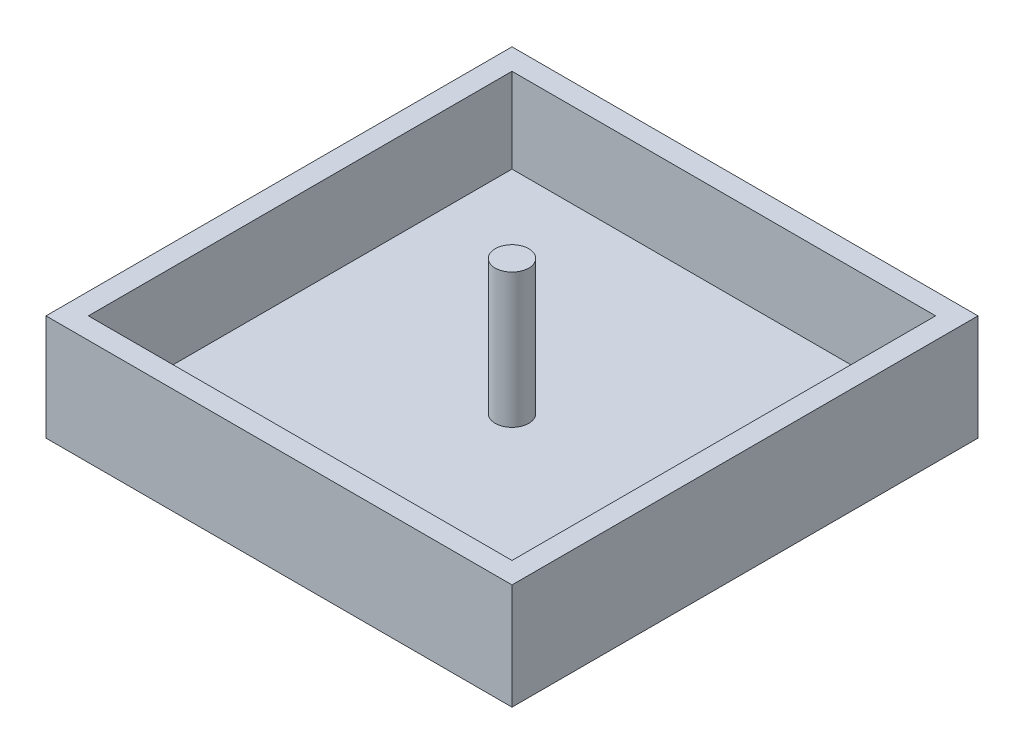
SolidWorks part; units mm, degrees
ref_plane "Plano frontal" through (0, 0, 0) normal (0, 0, 1) x (1, 0, 0)
ref_plane "Plano superior" through (0, 0, 0) normal (0, 1, 0) x (1, 0, 0)
ref_plane "Plano direito" through (0, 0, 0) normal (1, 0, 0) x (0, 0, -1)
sketch "Esboço1" plane through (0, 0, 0) normal (0, 1, 0) x (1, 0, 0)
  line L1 (-35.0121, 4.9879) -> (4.9879, 4.9879)
  line L2 (-35.0121, 4.9879) -> (-35.0121, -35.0121)
  line L3 (-35.0121, -35.0121) -> (4.9879, -35.0121)
  line L4 (4.9879, 4.9879) -> (4.9879, -35.0121)
extrude "Ressalto-extrusão1" add sketch "Esboço1" along normal blind 2
sketch "Esboço2" plane through (0, 0, 0) normal (0, -1, 0) x (1, 0, 0)
  line L0 (-35.0121, 35.0121) -> (-35.0121, -4.9879)
  line L1 (-37.0121, 35.0121) -> (-37.0121, -6.9879)
  line L2 (-35.0121, -4.9879) -> (4.9879, -4.9879)
  line L3 (-35.0121, -6.9879) -> (-37.0121, -6.9879)
  line L4 (-37.0121, -6.9879) -> (6.9879, -6.9879)
  line L5 (4.9879, -4.9879) -> (4.9879, 35.0121)
  line L6 (6.9879, -4.9879) -> (6.9879, -6.9879)
  line L7 (6.9879, -6.9879) -> (6.9879, 37.0121)
  line L8 (4.9879, 35.0121) -> (-35.0121, 35.0121)
  line L9 (4.9879, 37.0121) -> (6.9879, 37.0121)
  line L10 (6.9879, 37.0121) -> (-37.0121, 37.0121)
  line L11 (-37.0121, 35.0121) -> (-37.0121, 37.0121)
  line M3 (-35.0121, 35.0121) -> (-35.0121, -4.9879)
  line M4 (-35.0121, -4.9879) -> (4.9879, -4.9879)
  line M5 (4.9879, -4.9879) -> (4.9879, 35.0121)
  line M6 (4.9879, 35.0121) -> (-35.0121, 35.0121)
extrude "Ressalto-extrusão2" add sketch "Esboço2" against normal blind 10 contours L11 L1 L3 L4 L6 L7 L9 L10 M3 M6 M5 M4
sketch "Esboço3" plane through (0, 2, 0) normal (0, 1, 0) x (1, 0, 0)
  line L0 (4.9879, 4.9879) -> (-35.0121, 4.9879) construction
  line L1 (-35.0121, 4.9879) -> (-35.0121, -35.0121) construction
  circle A0 centre (-15.0121, -15.0121) radius 1.585
  dimension "D1" = 3.17
  dimension "D2" = 20
  dimension "D3" = 20
extrude "Ressalto-extrusão3" add sketch "Esboço3" along normal blind 12.7
